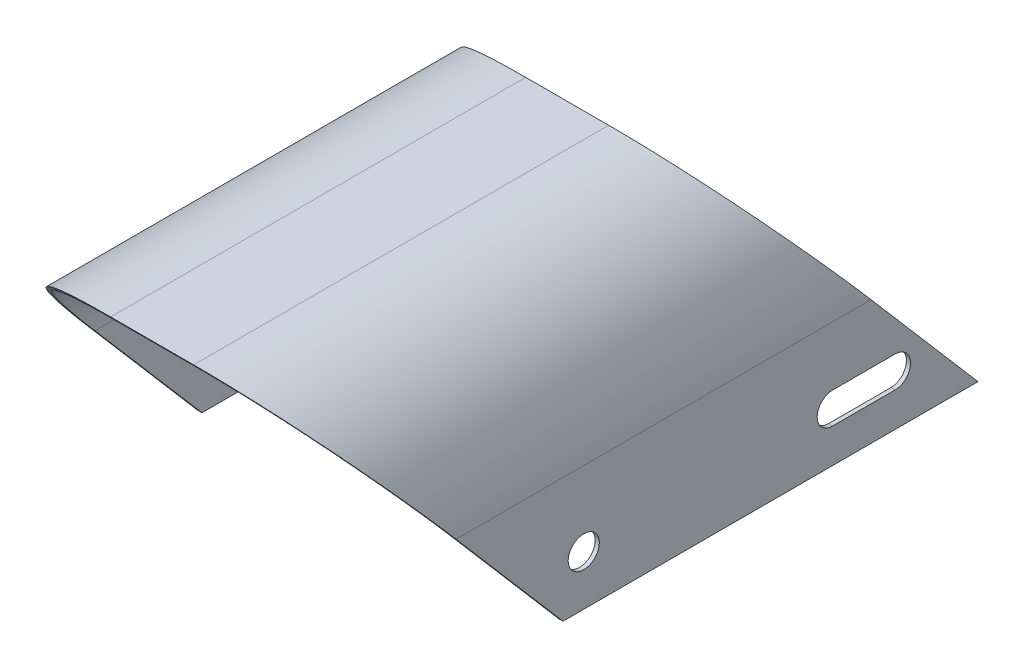
SolidWorks part; units mm, degrees
material "Magnesium Alloy"
ref_plane "Front Plane" through (0, 0, 0) normal (0, 0, 1) x (1, 0, 0)
ref_plane "Top Plane" through (0, 0, 0) normal (0, 1, 0) x (1, 0, 0)
ref_plane "Right Plane" through (0, 0, 0) normal (1, 0, 0) x (0, 0, -1)
sketch "Sketch1" plane through (0, 0, 0) normal (0, 0, 1) x (1, 0, 0)
  line L10 (-5.6029, 0) -> (-4.3329, 0)
  line L11 (-4.3329, 0) -> (-4.3329, 38.1)
  line L12 (-5.6029, 0) -> (-5.6029, 38.1)
  line L13 (37.5771, 80.01) -> (62.9771, 80.01)
  line L14 (37.5771, 81.28) -> (62.9771, 81.28)
  line L15 (106.1571, 38.1) -> (106.1571, 0)
  line L16 (106.1571, 0) -> (104.8871, 0)
  line L17 (104.8871, 0) -> (104.8871, 38.1)
  arc A6 (-4.3329, 38.1) -> (37.5771, 80.01) centre (37.5771, 38.1) cw
  arc A7 (-5.6029, 38.1) -> (37.5771, 81.28) centre (37.5771, 38.1) cw
  arc A8 (62.9771, 80.01) -> (104.8871, 38.1) centre (62.9771, 38.1) cw
  arc A9 (62.9771, 81.28) -> (106.1571, 38.1) centre (62.9771, 38.1) cw
  dimension "D1" = 1.27
  dimension "D2" = 38.1
  dimension "D5" = 38.1
  dimension "D3" = 41.91
  dimension "D4" = 25.4
extrude "Boss-Extrude1" add sketch "Sketch1" along normal blind 196.85
sketch "Sketch2" plane through (-5.6029, 0, 0) normal (-1, 0, 0) x (0, 0, 1)
  line L0 (0, 0) -> (69.85, 81.28)
  line L1 (196.85, 81.28) -> (0, 81.28) construction
  line L2 (69.85, 81.28) -> (0, 81.28)
  line L3 (0, -55) -> (0, 55) construction
  line L4 (0, 81.28) -> (0, 0)
  line L5 (196.85, 81.28) -> (127, 0)
  line L6 (196.85, 0) -> (0, 0) construction
  line L7 (127, 0) -> (196.85, 0)
  line L8 (196.85, 0) -> (196.85, 81.28)
  dimension "D1" = 69.85
  dimension "D2" = 69.85
extrude "Cut-Extrude1" cut sketch "Sketch2" against normal blind 152.4
sketch "Sketch3" plane through (-5.6029, 0, 0) normal (-1, 0, 0) x (0, 0, 1)
  line L0 (25.4, 20.0025) -> (44.45, 20.0025)
  line L1 (25.4, 10.4775) -> (44.45, 10.4775)
  line L2 (127, 0) -> (0, 0) construction
  arc A0 (25.4, 20.0025) -> (25.4, 10.4775) centre (25.4, 15.24) ccw
  arc A1 (44.45, 20.0025) -> (44.45, 10.4775) centre (44.45, 15.24) cw
  circle A2 centre (120.65, 15.24) radius 4.7625
  dimension "D2" = 4.7625
  dimension "D3" = 4.7625
  dimension "D6" = 9.525
  dimension "D1" = 19.05
  dimension "D4" = 15.24
  dimension "D5" = 25.4
  dimension "D7" = 76.2
extrude "Cut-Extrude2" cut sketch "Sketch3" against normal blind 152.4
